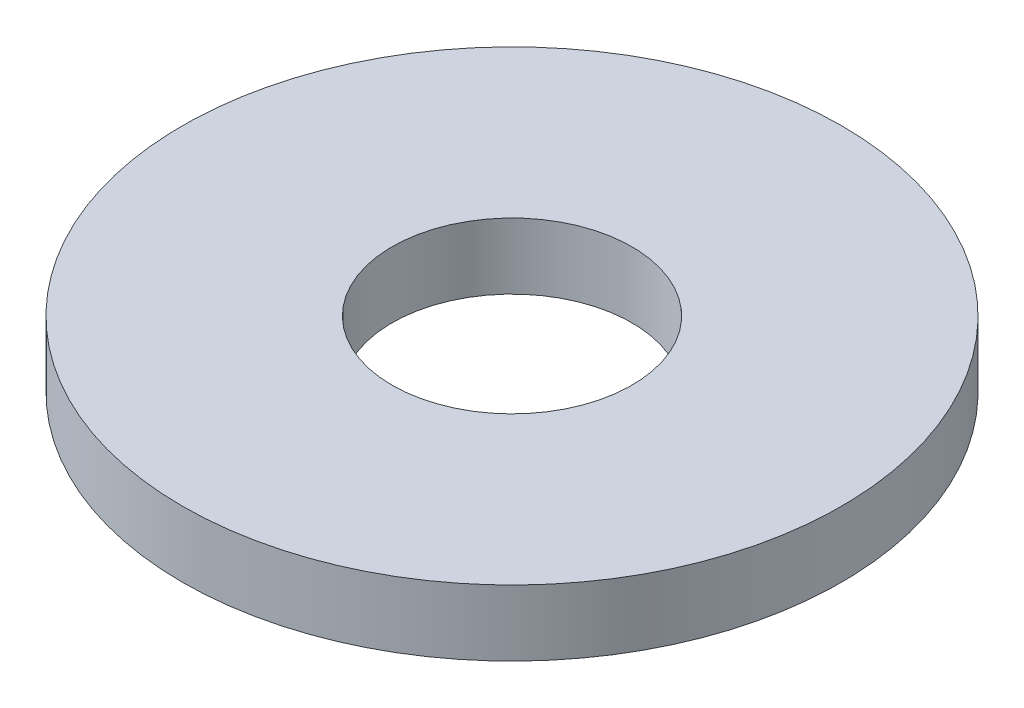
SolidWorks part; units mm, degrees
ref_plane "Front Plane" through (0, 0, 0) normal (0, 0, 1) x (1, 0, 0)
ref_plane "Top Plane" through (0, 0, 0) normal (0, 1, 0) x (1, 0, 0)
ref_plane "Right Plane" through (0, 0, 0) normal (1, 0, 0) x (0, 0, -1)
sketch "Sketch1" plane through (0, 0, 0) normal (0, 1, 0) x (1, 0, 0)
  circle A0 centre (0, 0) radius 4.55
  circle A1 centre (0, 0) radius 12.5
  dimension "D1" = 25
  dimension "D2" = 9.1
extrude "Boss-Extrude1" add sketch "Sketch1" along normal mid plane 2.5
